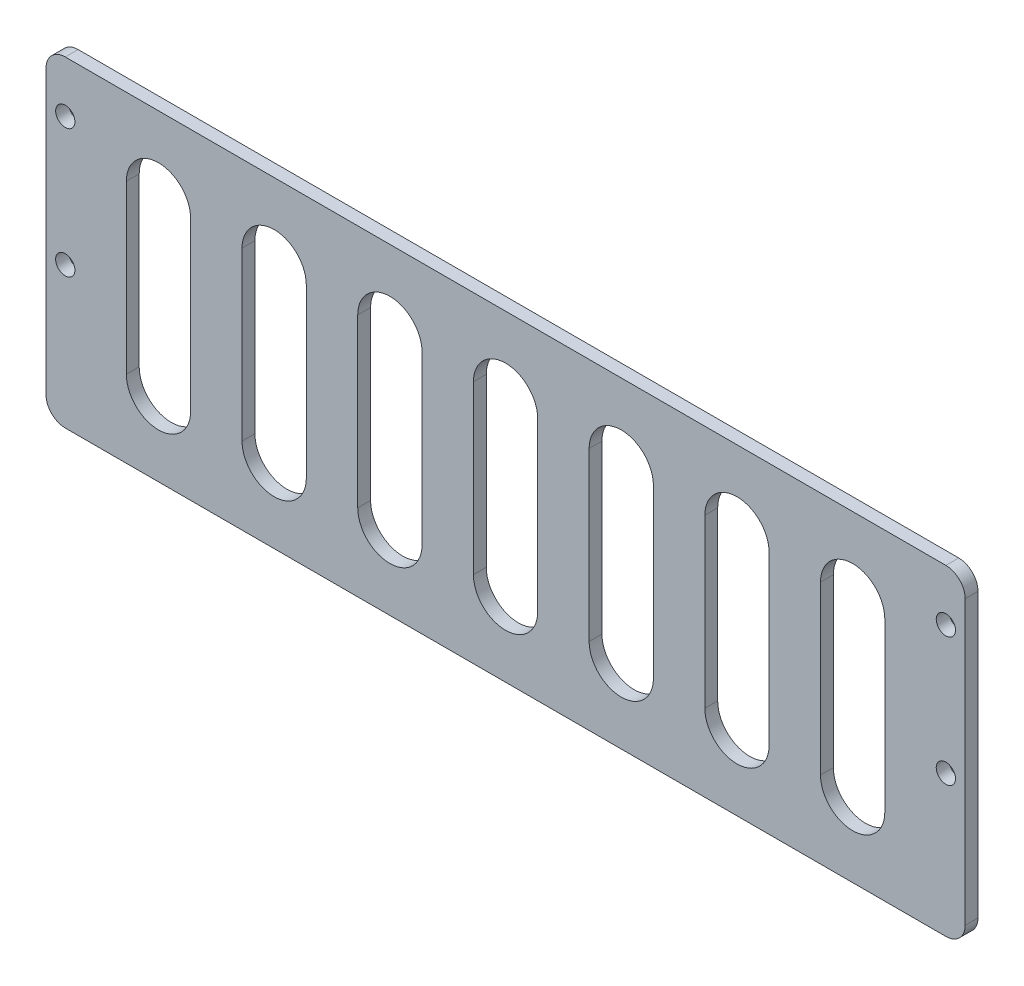
SolidWorks part; units mm, degrees
material "Thornel Mat VMA"
ref_plane "前视基准面" through (0, 0, 0) normal (0, 0, 1) x (1, 0, 0)
ref_plane "上视基准面" through (0, 0, 0) normal (0, 1, 0) x (1, 0, 0)
ref_plane "右视基准面" through (0, 0, 0) normal (1, 0, 0) x (0, 0, -1)
sketch "草图1" plane through (0, 0, 0) normal (0, 0, 1) x (1, 0, 0)
  line L1 (71.5, -25) -> (-71.5, -25)
  line L2 (71.5, -25) -> (71.5, 25)
  line L3 (71.5, 25) -> (-71.5, 25)
  line L4 (-71.5, -25) -> (-71.5, 25)
  line L5 (71.5, -25) -> (-71.5, 25) construction
  line L6 (71.5, 25) -> (-71.5, -25) construction
  point P0 (0, 0)
  dimension "D1" = 143
  dimension "D2" = 50
extrude "凸台-拉伸1" add sketch "草图1" along normal blind 2
fillet "圆角1" radius 3 4 edges at (71.5, 25, 1) (71.5, -25, 1) (-71.5, -25, 1) (-71.5, 25, 1)
sketch "草图2" plane through (0, 0, 2) normal (0, 0, 1) x (1, 0, 0)
  line L0 (0, 25) -> (0, -25) construction
  line L1 (68.5, 25) -> (-68.5, 25) construction
  line L2 (-68.5, -25) -> (68.5, -25) construction
  line L3 (-71.5, 0) -> (71.5, 0) construction
  line L4 (-71.5, 22) -> (-71.5, -22) construction
  line L5 (71.5, -22) -> (71.5, 22) construction
  line L6 (0, 13) -> (0, -13) construction
  line L7 (0, 13) -> (0, -13) construction
  line L8 (5, 13) -> (5, -13)
  line L9 (-5, 13) -> (-5, -13)
  line L10 (18, 13) -> (18, -13) construction
  line L11 (18, 13) -> (18, -13) construction
  line L12 (23, 13) -> (23, -13)
  line L13 (13, 13) -> (13, -13)
  line L14 (36, 13) -> (36, -13) construction
  line L15 (36, 13) -> (36, -13) construction
  line L16 (41, 13) -> (41, -13)
  line L17 (31, 13) -> (31, -13)
  line L18 (54, 13) -> (54, -13) construction
  line L19 (54, 13) -> (54, -13) construction
  line L20 (59, 13) -> (59, -13)
  line L21 (49, 13) -> (49, -13)
  line L22 (-54, 13) -> (-54, -13) construction
  line L23 (-36, 13) -> (-36, -13) construction
  line L24 (-18, 13) -> (-18, -13) construction
  line L25 (-54, 13) -> (-54, -13) construction
  line L26 (-59, 13) -> (-59, -13)
  line L27 (-49, 13) -> (-49, -13)
  line L28 (-36, 13) -> (-36, -13) construction
  line L29 (-41, 13) -> (-41, -13)
  line L30 (-31, 13) -> (-31, -13)
  line L31 (-18, 13) -> (-18, -13) construction
  line L32 (-23, 13) -> (-23, -13)
  line L33 (-13, 13) -> (-13, -13)
  arc A0 (5, 13) -> (-5, 13) centre (0, 13) ccw
  arc A1 (-5, -13) -> (5, -13) centre (0, -13) ccw
  arc A2 (23, 13) -> (13, 13) centre (18, 13) ccw
  arc A3 (13, -13) -> (23, -13) centre (18, -13) ccw
  arc A4 (41, 13) -> (31, 13) centre (36, 13) ccw
  arc A5 (31, -13) -> (41, -13) centre (36, -13) ccw
  arc A6 (59, 13) -> (49, 13) centre (54, 13) ccw
  arc A7 (49, -13) -> (59, -13) centre (54, -13) ccw
  arc A8 (-59, 13) -> (-49, 13) centre (-54, 13) cw
  arc A9 (-49, -13) -> (-59, -13) centre (-54, -13) cw
  arc A10 (-41, 13) -> (-31, 13) centre (-36, 13) cw
  arc A11 (-31, -13) -> (-41, -13) centre (-36, -13) cw
  arc A12 (-23, 13) -> (-13, 13) centre (-18, 13) cw
  arc A13 (-13, -13) -> (-23, -13) centre (-18, -13) cw
  point P12 (0, 0)
  point P16 (0, 0)
  point P21 (18, 0)
  point P24 (18, 0)
  point P29 (36, 0)
  point P32 (36, 0)
  point P37 (54, 0)
  point P40 (54, 0)
  point P50 (-54, 0)
  point P51 (-54, 0)
  point P56 (-36, 0)
  point P57 (-36, 0)
  point P62 (-18, 0)
  point P63 (-18, 0)
  dimension "D2" = 5
  dimension "D1" = 26
extrude "切除-拉伸1" cut sketch "草图2" against normal blind 10
sketch "草图7" plane through (0, 0, 0) normal (0, 0, -1) x (-1, 0, 0)
  line L0 (-71.5, -22) -> (-71.5, 22) construction
  circle A0 centre (-68.5, -3) radius 1.5
  circle A1 centre (-68.5, -3) radius 1.2 construction
  circle A2 centre (-68.5, 17) radius 1.5
  dimension "D1" = 3
  dimension "D3" = 20
  dimension "D2" = 0
extrude "切除-拉伸2" cut sketch "草图7" against normal blind 10
sketch "草图8" plane through (0, 0, 2) normal (0, 0, 1) x (1, 0, 0)
  line L0 (68.5, 25) -> (-68.5, 25) construction
  line L1 (0, 25) -> (0, -25) construction
  line L2 (-68.5, -25) -> (68.5, -25) construction
  point P0 (0, 25)
ref_plane "基准面1" through (0, 0, 0) normal (-1, 0, 0) x (0, -1, 0)
mirror "镜向2" about plane through (0, 0, 0) normal (-1, 0, 0) of "切除-拉伸2"
